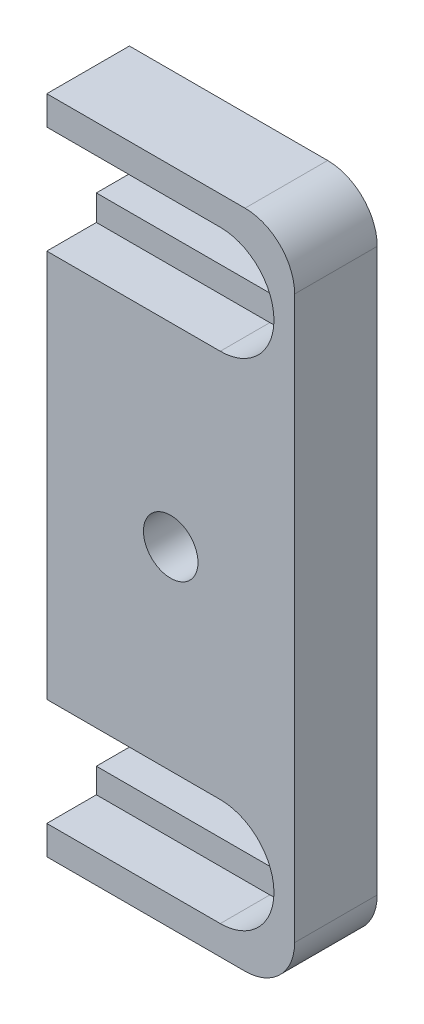
SolidWorks part; units mm, degrees
material "6061 Alloy"
ref_plane "Front" through (0, 0, 0) normal (0, 0, 1) x (1, 0, 0)
ref_plane "Top" through (0, 0, 0) normal (0, 1, 0) x (1, 0, 0)
ref_plane "Right" through (0, 0, 0) normal (1, 0, 0) x (0, 0, -1)
ref_plane "Plane1" through (0, 0, 5) normal (0, 0, 1) x (1, 0, 0)
sketch "Sketch1" plane through (0, 0, 5) normal (0, 0, 1) x (1, 0, 0)
  line L0 (15, 0) -> (0, 0)
  line L1 (0, 0) -> (0, -40)
  line L2 (0, -40) -> (15, -40)
  line L3 (15, -40) -> (15, 0)
extrude "Boss-Extrude1" add sketch "Sketch1" against normal blind 5
sketch "Sketch2" plane through (0, 0, 5) normal (0, 0, 1) x (1, 0, 0)
  line L0 (0, -8.25) -> (10.5, -8.25)
  line L1 (10.5, -1.75) -> (0, -1.75)
  line L2 (0, -1.75) -> (0, -8.25)
  arc A0 (10.5, -8.25) -> (10.5, -1.75) centre (10.5, -5) ccw
extrude "Cut-Extrude1" cut sketch "Sketch2" against normal blind 3
sketch "Sketch3" plane through (0, 0, 2) normal (0, 0, 1) x (1, 0, 0)
  line L0 (0, -3.3) -> (0, -6.7)
  line L1 (0, -6.7) -> (10.5, -6.7)
  line L2 (10.5, -3.3) -> (0, -3.3)
  arc A0 (10.5, -6.7) -> (10.5, -3.3) centre (10.5, -5) ccw
extrude "Cut-Extrude2" cut sketch "Sketch3" against normal through all
sketch "Sketch4" plane through (0, 0, 5) normal (0, 0, 1) x (1, 0, 0)
  line L0 (10.5, -31.75) -> (0, -31.75)
  line L1 (0, -31.75) -> (0, -38.25)
  line L2 (0, -38.25) -> (10.5, -38.25)
  arc A0 (10.5, -38.25) -> (10.5, -31.75) centre (10.5, -35) ccw
extrude "Cut-Extrude3" cut sketch "Sketch4" against normal blind 3
sketch "Sketch5" plane through (0, 0, 0) normal (0, 0, -1) x (-1, 0, 0)
  line L0 (0, -36.75) -> (0, -33.25)
  line L1 (0, -33.25) -> (-10.5, -33.25)
  line L2 (-10.5, -36.75) -> (0, -36.75)
  arc A0 (-10.5, -33.25) -> (-10.5, -36.75) centre (-10.5, -35) ccw
extrude "Cut-Extrude4" cut sketch "Sketch5" against normal through all
hole_wizard "M4x0.7 Tapped Hole1" positions "Sketch7" profile "Sketch6" tap size "M4x0.7" standard "ANSI Metric" end condition through all
sketch "Sketch7" plane through (0, 0, 5) normal (0, 0, 1) x (1, 0, 0)
  point P0 (7.5, -20)
sketch "Sketch6" plane through (7.5, -20, 5) normal (1, 0, 0) x (0, -1, 0)
  line L0 (0, 0) -> (0, 5)
  line L1 (0, 5) -> (1.65, 5)
  line L2 (1.65, 5) -> (1.65, 0)
  line L5 (1.65, 0) -> (0, 0)
  line L11 (0, -6.35) -> (0, 107.95) construction
  dimension "Thru Tap Drill Dia." = 3.3
  dimension "Thru Tap Drill Depth" = 5
fillet "Fillet1" radius 3 2 edges at (15, -40, 2.5) (15, 0, 2.5)
